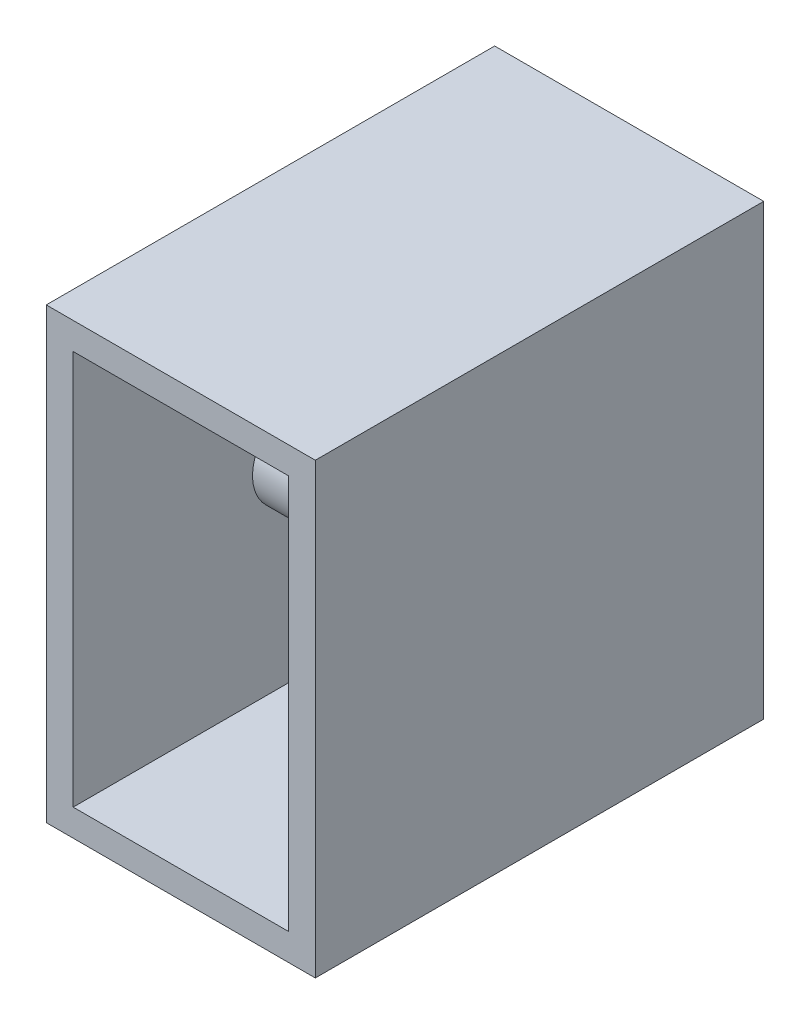
SolidWorks part; units mm, degrees
ref_plane "Front Plane" through (0, 0, 0) normal (0, 0, 1) x (1, 0, 0)
ref_plane "Top Plane" through (0, 0, 0) normal (0, 1, 0) x (1, 0, 0)
ref_plane "Right Plane" through (0, 0, 0) normal (1, 0, 0) x (0, 0, -1)
sketch "Sketch1" plane through (0, 0, 0) normal (0, 0, 1) x (1, 0, 0)
  line L1 (0, 0) -> (30, 0)
  line L2 (0, 0) -> (0, 50)
  line L3 (0, 50) -> (30, 50)
  line L4 (30, 0) -> (30, 50)
  dimension "D1" = 50
  dimension "D2" = 30
extrude "Extrude-Thin1" add sketch "Sketch1" along normal blind 50 thin thin type one direction reverse wall 3
sketch "Sketch2" plane through (30, 0, 0) normal (1, 0, 0) x (0, 0, -1)
  line L0 (0, 0) -> (0, 50) construction
  line L1 (-50, 50) -> (0, 50) construction
  circle A0 centre (-25, 25) radius 5
  dimension "D1" = 10
  dimension "D2" = 25
  dimension "D3" = 25
extrude "Boss-Extrude1" add sketch "Sketch2" against normal through all
